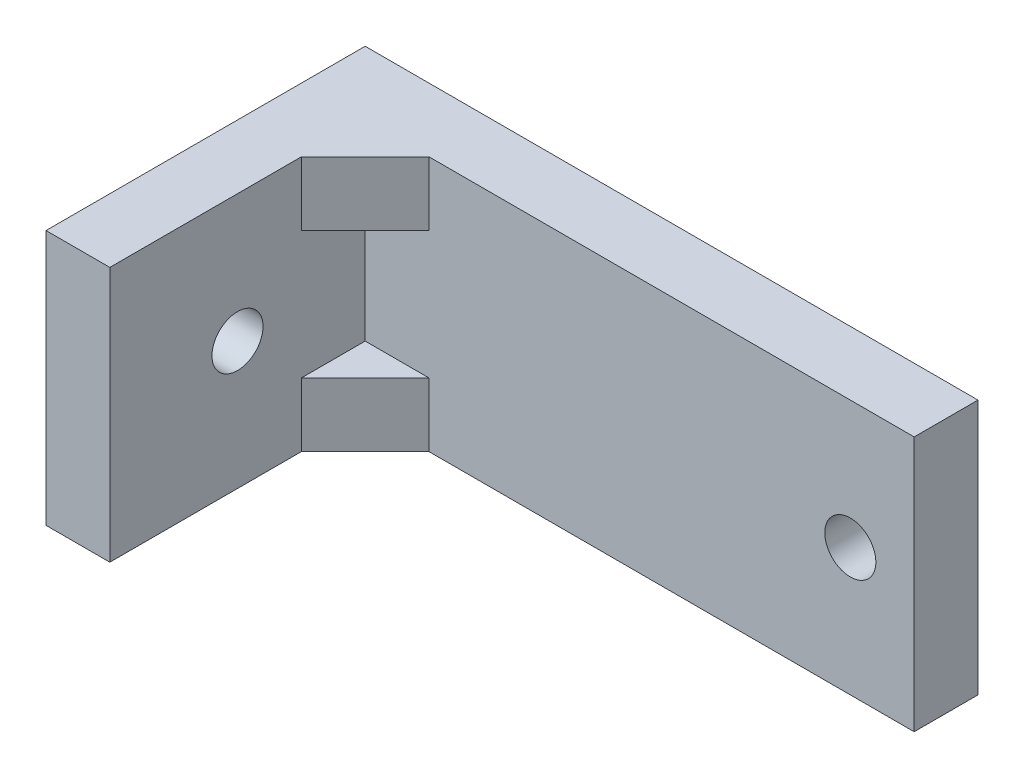
SolidWorks part; units mm, degrees
ref_plane "Front Plane" through (0, 0, 0) normal (0, 0, 1) x (1, 0, 0)
ref_plane "Top Plane" through (0, 0, 0) normal (0, 1, 0) x (1, 0, 0)
ref_plane "Right Plane" through (0, 0, 0) normal (1, 0, 0) x (0, 0, -1)
sketch "Sketch1" plane through (0, 0, 0) normal (0, 0, 1) x (1, 0, 0)
  line L1 (-24, 10) -> (24, 10)
  line L2 (-24, 10) -> (-24, -10)
  line L3 (-24, -10) -> (24, -10)
  line L4 (24, 10) -> (24, -10)
  line L5 (-24, 10) -> (24, -10) construction
  line L6 (-24, -10) -> (24, 10) construction
  point P0 (0, 0)
  dimension "D1" = 48
  dimension "D2" = 20
extrude "Boss-Extrude1" add sketch "Sketch1" along normal blind 5
sketch "Sketch2" plane through (0, 0, 5) normal (0, 0, 1) x (1, 0, 0)
  line L0 (-24, -10) -> (24, -10) construction
  line L1 (-24, 10) -> (-19, 10)
  line L2 (-24, 10) -> (-24, -10)
  line L3 (-24, -10) -> (-19, -10)
  line L4 (-19, 10) -> (-19, -10)
  dimension "D1" = 5
extrude "Boss-Extrude2" add sketch "Sketch2" along normal blind 20
sketch "Sketch3" plane through (-19, 0, 0) normal (1, 0, 0) x (0, 0, -1)
  line L0 (-25, -10) -> (-25, 10) construction
  line L1 (-25, -10) -> (-5, -10) construction
  circle A0 centre (-15, 0) radius 2
  dimension "D1" = 4
  dimension "D3" = 10
  dimension "D2" = 10
extrude "Cut-Extrude1" cut sketch "Sketch3" against normal through all
sketch "Sketch4" plane through (0, 0, 0) normal (0, 0, -1) x (-1, 0, 0)
  line L0 (24, 10) -> (24, -10) construction
  circle A0 centre (-90, 0) radius 2
  dimension "D1" = 4
  dimension "D2" = 114
sketch "Sketch5" plane through (-19, 0, 0) normal (1, 0, 0) x (0, 0, -1)
  line L1 (-5, -10) -> (-10, -10)
  line L2 (-5, -10) -> (-5, -5)
  line L3 (-5, -5) -> (-10, -5)
  line L4 (-10, -10) -> (-10, -5)
  line L5 (-5, 10) -> (-10, 10)
  line L6 (-5, 10) -> (-5, 5)
  line L7 (-5, 5) -> (-10, 5)
  line L8 (-10, 10) -> (-10, 5)
  dimension "D1" = 5
  dimension "D2" = 5
  dimension "D3" = 5
  dimension "D4" = 5
extrude "Boss-Extrude3" add sketch "Sketch5" along normal blind 5
sketch "Sketch6" plane through (0, 10, 0) normal (0, 1, 0) x (1, 0, 0)
  line L0 (-14, -5) -> (-19, -10)
  line L1 (-19, -10) -> (-14, -10)
  line L2 (-14, -10) -> (-14, -5)
extrude "Cut-Extrude3" cut sketch "Sketch6" against normal through all
sketch "Sketch7" plane through (0, 0, 0) normal (0, 0, -1) x (-1, 0, 0)
  line L0 (24, 10) -> (24, -10) construction
  circle A0 centre (-19, 0) radius 2
  dimension "D1" = 4
  dimension "D2" = 43
extrude "Cut-Extrude4" cut sketch "Sketch7" against normal through all
